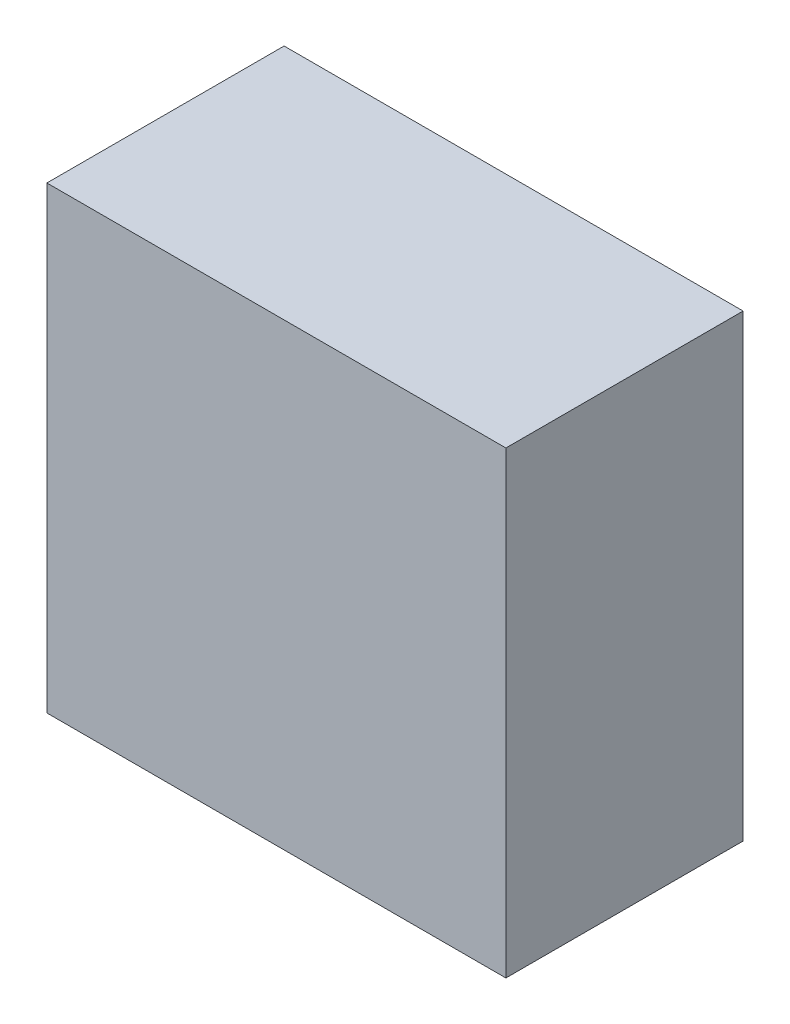
SolidWorks part; units mm, degrees
ref_plane "Front Plane" through (0, 0, 0) normal (0, 0, 1) x (1, 0, 0)
ref_plane "Top Plane" through (0, 0, 0) normal (0, 1, 0) x (1, 0, 0)
ref_plane "Right Plane" through (0, 0, 0) normal (1, 0, 0) x (0, 0, -1)
sketch "Sketch1" plane through (0, 0, 0) normal (0, 0, 1) x (1, 0, 0)
  line L1 (0, 0) -> (40.15, 0)
  line L2 (0, 0) -> (0, 40.15)
  line L3 (0, 40.15) -> (40.15, 40.15)
  line L4 (40.15, 0) -> (40.15, 40.15)
  dimension "D1" = 40.15
  dimension "D2" = 40.15
extrude "Boss-Extrude1" add sketch "Sketch1" along normal blind 20.75 contours L3 L4 L1 L2
